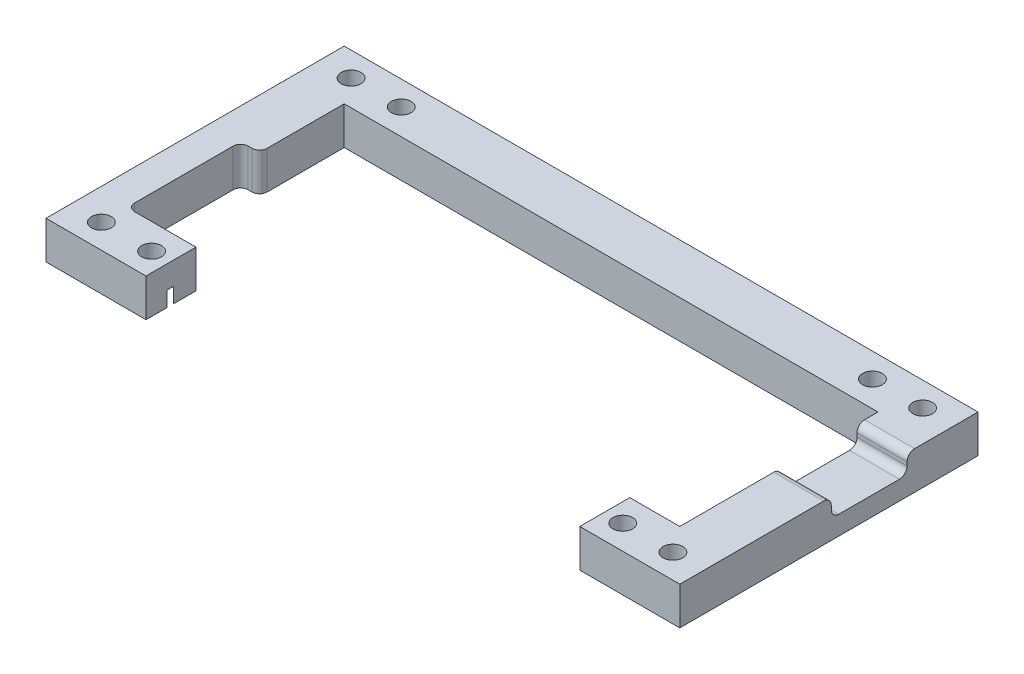
SolidWorks part; units mm, degrees
ref_plane "Front Plane" through (0, 0, 0) normal (0, 0, 1) x (1, 0, 0)
ref_plane "Top Plane" through (0, 0, 0) normal (0, 1, 0) x (1, 0, 0)
ref_plane "Right Plane" through (0, 0, 0) normal (1, 0, 0) x (0, 0, -1)
sketch "Sketch1" plane through (0, 0, 0) normal (0, 1, 0) x (1, 0, 0)
  line L0 (181.4198, 36.9979) -> (75.1552, 36.9979) construction
  line L1 (75.1552, 11.9979) -> (83.5372, 11.9979)
  line L2 (75.1552, 11.9979) -> (75.1552, 61.9979)
  line L3 (75.1552, 61.9979) -> (83.5372, 61.9979)
  line L4 (83.5372, 11.9979) -> (83.5372, 61.9979)
  line L5 (83.5372, 61.9979) -> (91.9192, 61.9979)
  line L6 (83.5372, 61.9979) -> (83.5372, 53.6159)
  line L7 (83.5372, 53.6159) -> (91.9192, 53.6159)
  line L8 (167.7876, 16.0648) -> (186.7138, 16.0648) construction
  line L9 (83.5372, 11.9979) -> (91.9192, 11.9979)
  line L10 (83.5372, 11.9979) -> (83.5372, 20.3799)
  line L11 (83.5372, 20.3799) -> (91.9192, 20.3799)
  line L12 (91.9192, 11.9979) -> (91.9192, 20.3799)
  line L13 (75.1552, 61.9979) -> (181.4198, 61.9979)
  line L17 (181.4198, 61.9979) -> (173.0378, 61.9979)
  line L18 (181.4198, 61.9979) -> (181.4198, 11.9979)
  line L19 (181.4198, 11.9979) -> (173.0378, 11.9979)
  line L20 (173.0378, 61.9979) -> (173.0378, 11.9979)
  line L21 (173.0378, 61.9979) -> (164.6558, 61.9979)
  line L22 (173.0378, 61.9979) -> (173.0378, 53.6159)
  line L23 (173.0378, 53.6159) -> (164.6558, 53.6159)
  line L25 (173.0378, 11.9979) -> (164.6558, 11.9979)
  line L26 (173.0378, 11.9979) -> (173.0378, 20.3799)
  line L27 (173.0378, 20.3799) -> (164.6558, 20.3799)
  line L28 (164.6558, 11.9979) -> (164.6558, 20.3799)
  line L29 (128.2875, 61.9979) -> (128.2875, -9.1774) construction
  line L30 (164.6558, 53.6159) -> (91.9192, 53.6159)
  circle A0 centre (167.7876, 57.931) radius 1.651
  circle A1 centre (167.7876, 16.0648) radius 1.651
  circle A2 centre (88.7875, 16.0648) radius 1.651
  circle A3 centre (88.7875, 57.931) radius 1.651
  circle A4 centre (176.2028, 16.0648) radius 1.651
  circle A5 centre (80.3722, 16.0648) radius 1.651
  circle A6 centre (80.3722, 57.931) radius 1.651
  circle A7 centre (176.2028, 57.931) radius 1.651
  point P32 (91.9192, 16.1889)
  point P34 (88.7875, 57.931)
  point P35 (88.7875, 16.0648)
  dimension "D15" = 3.302
  dimension "D16" = 3.1342
  dimension "D6" = 79.0001
  dimension "D18" = 3.302
  dimension "D2" = 47.9153
  dimension "D1" = 8.382
  dimension "D3" = 50
  dimension "D4" = 8.382
  dimension "D5" = 50
  dimension "D7" = 8.382
  dimension "D8" = 8.382
  dimension "D9" = 8.382
  dimension "D10" = 8.382
  dimension "D11" = 8.382
  dimension "D12" = 8.382
  dimension "D13" = 8.382
  dimension "D14" = 8.382
  dimension "D17" = 3.1317
extrude "Boss-Extrude1" add sketch "Sketch1" along normal blind 6.35
sketch "Sketch2" plane through (181.4198, 0, 0) normal (1, 0, 0) x (0, 0, -1)
  line L0 (61.9979, 6.35) -> (11.9979, 6.35) construction
  line L1 (37.3979, 6.35) -> (50.0979, 6.35)
  line L2 (37.3979, 6.35) -> (37.3979, 3.175)
  line L3 (37.3979, 3.175) -> (50.0979, 3.175)
  line L4 (50.0979, 6.35) -> (50.0979, 3.175)
  line L5 (11.9979, 6.35) -> (11.9979, 0) construction
  dimension "D1" = 25.4
  dimension "D2" = 12.7
  dimension "D3" = 3.175
extrude "Cut-Extrude7" cut sketch "Sketch2" against normal blind 8.89 contours L2 L3 L4 L1
fillet "Fillet2" radius 1.27 4 edges at (177.2288, 6.35, -37.3979) (177.2288, 6.35, -50.0979) (177.2288, 3.175, -50.0979) (177.2288, 3.175, -37.3979)
sketch "Sketch4" plane through (0, 6.35, 0) normal (0, 1, 0) x (1, 0, 0)
  line L1 (83.5372, 20.3799) -> (80.3622, 20.3799)
  line L2 (83.5372, 20.3799) -> (83.5372, 39.4299)
  line L3 (83.5372, 39.4299) -> (80.3622, 39.4299)
  line L4 (80.3622, 20.3799) -> (80.3622, 39.4299)
  dimension "D1" = 3.175
  dimension "D2" = 19.05
extrude "Cut-Extrude8" cut sketch "Sketch4" against normal through all
fillet "Fillet3" radius 1.27 3 edges at (80.3622, 3.175, -20.3799) (80.3622, 3.175, -39.4299) (83.5372, 3.175, -39.4299)
sketch "Sketch5" plane through (0, 0, 0) normal (0, -1, 0) x (1, 0, 0)
  circle A0 centre (88.7875, -16.0648) radius 3.175
  circle A1 centre (88.7875, -57.931) radius 3.175
  circle A2 centre (167.7876, -57.931) radius 3.175
  circle A3 centre (167.7876, -16.0648) radius 3.175
  dimension "D1" = 6.35
  dimension "D2" = 6.35
  dimension "D3" = 6.35
  dimension "D4" = 6.35
extrude "Cut-Extrude9" cut sketch "Sketch5" against normal blind 2.54
